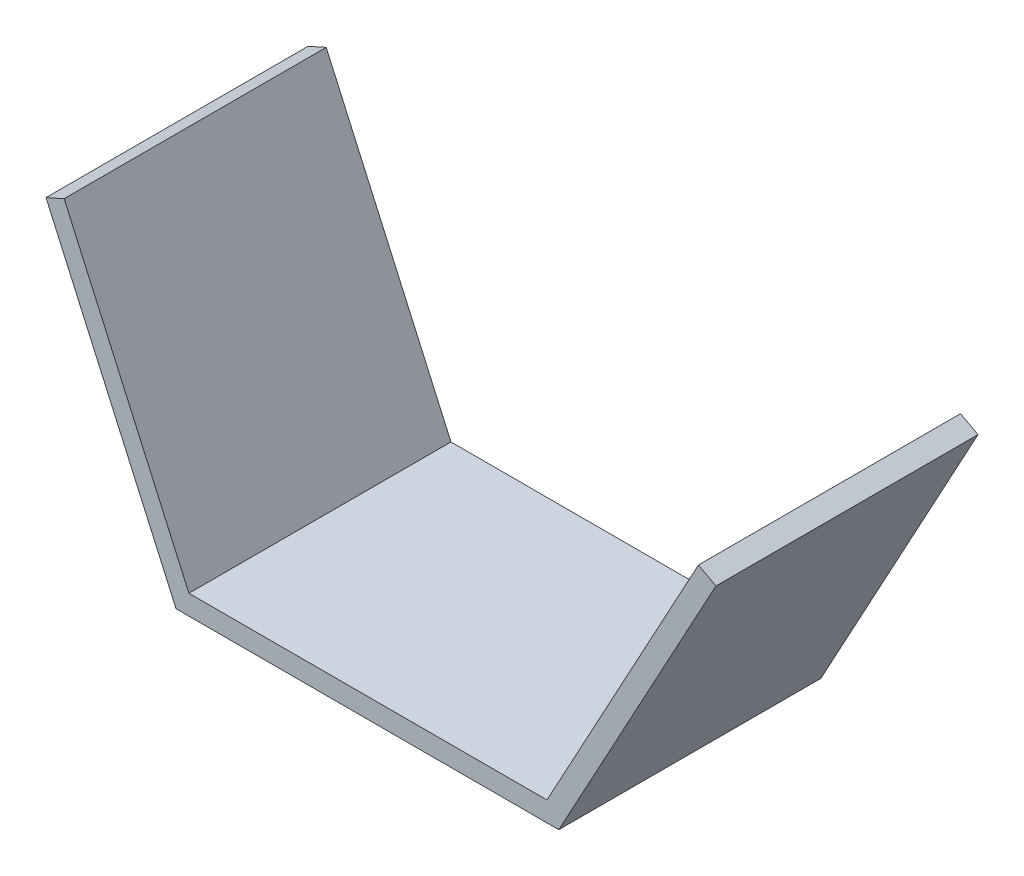
SolidWorks part; units mm, degrees
ref_plane "Ön Düzlem" through (0, 0, 0) normal (0, 0, 1) x (1, 0, 0)
ref_plane "Üst Düzlem" through (0, 0, 0) normal (0, 1, 0) x (1, 0, 0)
ref_plane "Sağ Düzlem" through (0, 0, 0) normal (1, 0, 0) x (0, 0, -1)
sketch "Çizim1" plane through (0, 0, 0) normal (0, 0, 1) x (1, 0, 0)
  line L0 (-58.5024, 23.386) -> (-27.0716, -46.9592)
  line L1 (63.105, -46.9592) -> (101.271, 23.386)
  line L2 (-27.0716, -46.9592) -> (63.105, -46.9592)
extrude "Ekstrüzyon-İnce1" add sketch "Çizim1" along normal blind 66 thin
